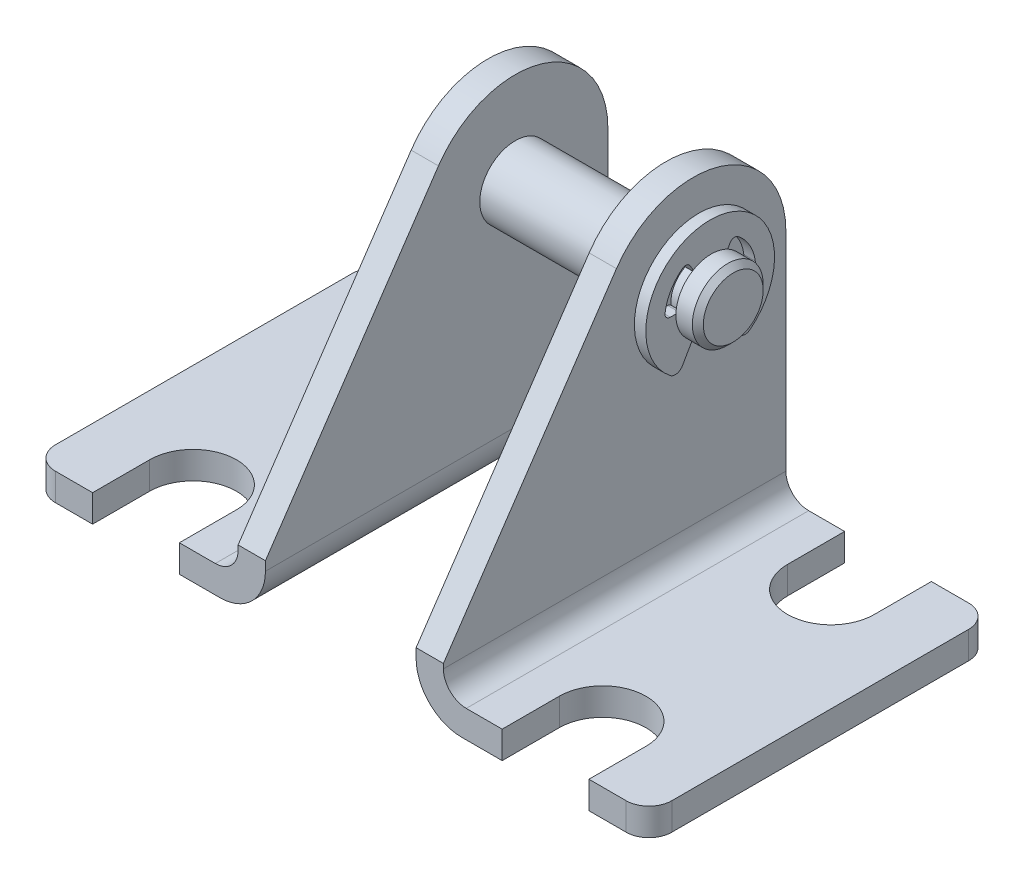
SolidWorks part; units mm, degrees
ref_plane "Front Plane" through (0, 0, 0) normal (0, 0, 1) x (1, 0, 0)
ref_plane "Top Plane" through (0, 0, 0) normal (0, 1, 0) x (1, 0, 0)
ref_plane "Right Plane" through (0, 0, 0) normal (1, 0, 0) x (0, 0, -1)
sketch "Sketch1" plane through (0, 0, 0) normal (0, 1, 0) x (1, 0, 0)
  line L0 (-17.145, 0) -> (17.145, 0) construction
  line L1 (-17.145, 5.1562) -> (-13.8049, 5.1562)
  line L2 (-17.145, 5.1562) -> (-17.145, -13.8938)
  line L3 (-17.145, -13.8938) -> (-13.8049, -13.8938)
  line L4 (17.145, 5.1562) -> (17.145, -13.8938)
  line L5 (-4.191, 5.1562) -> (-4.191, -13.8938)
  line L6 (4.191, 5.1562) -> (4.191, -13.8938)
  line L7 (4.191, 5.1562) -> (8.9789, 5.1562)
  line L8 (4.191, -13.8938) -> (8.9789, -13.8938)
  line L9 (-5.7099, 5.1562) -> (-5.7099, -13.8938) construction
  line L10 (-4.191, 5.1562) -> (4.191, 5.1562) construction
  line L11 (-4.191, -13.8938) -> (4.191, -13.8938) construction
  line L12 (0, 5.1562) -> (0, 0) construction
  line L13 (-13.8049, 1.9812) -> (-13.8049, 5.1562)
  line L14 (-8.9789, 1.9812) -> (-8.9789, 5.1562)
  line L15 (8.9789, 1.9812) -> (8.9789, 5.1562)
  line L16 (13.8049, 1.9812) -> (13.8049, 5.1562)
  line L17 (13.8049, -10.7188) -> (13.8049, -13.8938)
  line L18 (8.9789, -10.7188) -> (8.9789, -13.8938)
  line L19 (-8.9789, -10.7188) -> (-8.9789, -13.8938)
  line L20 (-13.8049, -10.7188) -> (-13.8049, -13.8938)
  line L21 (-8.9789, -13.8938) -> (-4.191, -13.8938)
  line L22 (13.8049, -13.8938) -> (17.145, -13.8938)
  line L23 (13.8049, 5.1562) -> (17.145, 5.1562)
  line L24 (-8.9789, 5.1562) -> (-4.191, 5.1562)
  line L25 (5.7099, 5.1562) -> (5.7099, -13.8938) construction
  arc A0 (-13.8049, 1.9812) -> (-8.9789, 1.9812) centre (-11.3919, 1.9812) ccw
  arc A1 (-8.9789, -10.7188) -> (-13.8049, -10.7188) centre (-11.3919, -10.7188) ccw
  arc A2 (13.8049, -10.7188) -> (8.9789, -10.7188) centre (11.3919, -10.7188) ccw
  arc A3 (8.9789, 1.9812) -> (13.8049, 1.9812) centre (11.3919, 1.9812) ccw
  dimension "D1" = 22.7838
  dimension "A" = 5.1562
  dimension "C" = 8.382
  dimension "D" = 1.5189
  dimension "K" = 34.29
  dimension "J" = 19.05
  dimension "I" = 3.175
  dimension "H" = 12.7
  dimension "G" = 4.826
sketch "Sketch2" plane through (0, 0, 0) normal (1, 0, 0) x (0, 0, -1)
  line L0 (-13.8938, 0) -> (5.1562, 0)
  line L1 (0, 14.3637) -> (0, 0) construction
  line L2 (-13.8938, 0) -> (-13.8938, 3.048)
  line L3 (-13.8938, 3.048) -> (-4.2689, 17.2556)
  line L4 (5.1562, 14.3637) -> (5.1562, 0)
  arc A0 (-4.2689, 17.2556) -> (5.1562, 14.3637) centre (0, 14.3637) cw
  circle A1 centre (0, 14.3637) radius 1.9698
  dimension "Pin Dia" = 3.9395
  dimension "D1" = 3.048
  dimension "E" = 19.5199
  dimension "F" = 14.3637
sketch "Sketch3" plane through (0, 0, 0) normal (0, 1, 0) x (1, 0, 0)
  line L12 (8.9789, -13.8938) -> (8.9789, -10.7188)
  line L13 (13.8049, -10.7188) -> (13.8049, -13.8938)
  line L14 (13.8049, -13.8938) -> (17.145, -13.8938)
  line L15 (17.145, -13.8938) -> (17.145, 5.1562)
  line L16 (17.145, 5.1562) -> (13.8049, 5.1562)
  line L17 (13.8049, 5.1562) -> (13.8049, 1.9812)
  line L18 (8.9789, 1.9812) -> (8.9789, 5.1562)
  line L19 (8.9789, 5.1562) -> (4.191, 5.1562)
  line L20 (4.191, 5.1562) -> (4.191, -13.8938)
  line L21 (4.191, -13.8938) -> (8.9789, -13.8938)
  line L22 (8.9789, -13.8938) -> (8.9789, -10.7188)
  line L23 (13.8049, -10.7188) -> (13.8049, -13.8938)
  line L24 (13.8049, -13.8938) -> (17.145, -13.8938)
  line L25 (17.145, -13.8938) -> (17.145, 5.1562)
  line L26 (17.145, 5.1562) -> (13.8049, 5.1562)
  line L27 (13.8049, 5.1562) -> (13.8049, 1.9812)
  line L28 (8.9789, 1.9812) -> (8.9789, 5.1562)
  line L29 (8.9789, 5.1562) -> (4.191, 5.1562)
  line L30 (4.191, 5.1562) -> (4.191, -13.8938)
  line L31 (4.191, -13.8938) -> (8.9789, -13.8938)
  line L32 (-17.145, -13.8938) -> (-13.8049, -13.8938)
  line L33 (-17.145, 5.1562) -> (-17.145, -13.8938)
  line L34 (-13.8049, 5.1562) -> (-17.145, 5.1562)
  line L35 (-13.8049, 1.9812) -> (-13.8049, 5.1562)
  line L36 (-8.9789, 5.1562) -> (-8.9789, 1.9812)
  line L37 (-4.191, 5.1562) -> (-8.9789, 5.1562)
  line L38 (-4.191, -13.8938) -> (-4.191, 5.1562)
  line L39 (-8.9789, -13.8938) -> (-4.191, -13.8938)
  line L40 (-8.9789, -10.7188) -> (-8.9789, -13.8938)
  line L41 (-13.8049, -13.8938) -> (-13.8049, -10.7188)
  line L42 (-17.145, -13.8938) -> (-13.8049, -13.8938)
  line L43 (-17.145, 5.1562) -> (-17.145, -13.8938)
  line L44 (-13.8049, 5.1562) -> (-17.145, 5.1562)
  line L45 (-13.8049, 1.9812) -> (-13.8049, 5.1562)
  line L46 (-8.9789, 5.1562) -> (-8.9789, 1.9812)
  line L47 (-4.191, 5.1562) -> (-8.9789, 5.1562)
  line L48 (-4.191, -13.8938) -> (-4.191, 5.1562)
  line L49 (-8.9789, -13.8938) -> (-4.191, -13.8938)
  line L50 (-8.9789, -10.7188) -> (-8.9789, -13.8938)
  line L51 (-13.8049, -13.8938) -> (-13.8049, -10.7188)
  arc A2 (13.8049, -10.7188) -> (8.9789, -10.7188) centre (11.3919, -10.7188) ccw
  arc A3 (8.9789, 1.9812) -> (13.8049, 1.9812) centre (11.3919, 1.9812) ccw
  arc A4 (13.8049, -10.7188) -> (8.9789, -10.7188) centre (11.3919, -10.7188) ccw
  arc A5 (8.9789, 1.9812) -> (13.8049, 1.9812) centre (11.3919, 1.9812) ccw
  arc A6 (-13.8049, 1.9812) -> (-8.9789, 1.9812) centre (-11.3919, 1.9812) ccw
  arc A7 (-8.9789, -10.7188) -> (-13.8049, -10.7188) centre (-11.3919, -10.7188) ccw
  arc A8 (-13.8049, 1.9812) -> (-8.9789, 1.9812) centre (-11.3919, 1.9812) ccw
  arc A9 (-8.9789, -10.7188) -> (-13.8049, -10.7188) centre (-11.3919, -10.7188) ccw
  dimension "D1" = 0
  dimension "D2" = 0
extrude "Boss-Extrude1" add sketch "Sketch3" along normal blind 1.5189
sketch "Sketch4" plane through (-4.191, 0, 0) normal (1, 0, 0) x (0, 0, -1)
  line L6 (-13.8938, 0) -> (5.1562, 0)
  line L7 (5.1562, 0) -> (5.1562, 14.3637)
  line L8 (-4.2689, 17.2556) -> (-13.8938, 3.048)
  line L12 (-13.8938, 3.048) -> (-13.8938, 0)
  line L13 (-13.8938, 0) -> (5.1562, 0)
  line L14 (5.1562, 0) -> (5.1562, 14.3637)
  line L15 (-4.2689, 17.2556) -> (-13.8938, 3.048)
  line L16 (-13.8938, 3.048) -> (-13.8938, 0)
  circle A1 centre (0, 14.3637) radius 1.9698
  circle A3 centre (0, 14.3637) radius 1.9698
  arc A5 (5.1562, 14.3637) -> (-4.2689, 17.2556) centre (0, 14.3637) ccw
  arc A6 (5.1562, 14.3637) -> (-4.2689, 17.2556) centre (0, 14.3637) ccw
  dimension "D1" = 0
  dimension "D2" = 0
extrude "Boss-Extrude2" add sketch "Sketch4" against normal up to vertex (1.5189 mm away) up to point (-5.7099, 0, -5.1562)
sketch "Sketch5" plane through (4.191, 0, 0) normal (-1, 0, 0) x (0, 0, 1)
  line L4 (-5.1562, 0) -> (13.8938, 0)
  line L5 (-5.1562, 14.3637) -> (-5.1562, 0)
  line L6 (13.8938, 3.048) -> (4.2689, 17.2556)
  line L7 (13.8938, 0) -> (13.8938, 3.048)
  line L8 (-5.1562, 0) -> (13.8938, 0)
  line L9 (-5.1562, 14.3637) -> (-5.1562, 0)
  line L10 (13.8938, 3.048) -> (4.2689, 17.2556)
  line L11 (13.8938, 0) -> (13.8938, 3.048)
  circle A1 centre (0, 14.3637) radius 1.9698
  circle A2 centre (0, 14.3637) radius 1.9698
  arc A3 (4.2689, 17.2556) -> (-5.1562, 14.3637) centre (0, 14.3637) ccw
  arc A4 (4.2689, 17.2556) -> (-5.1562, 14.3637) centre (0, 14.3637) ccw
  dimension "D1" = 0
  dimension "D2" = 0
extrude "Boss-Extrude3" add sketch "Sketch5" against normal up to vertex (1.5189 mm away) up to point (5.7099, 0, -5.1562)
fillet "Fillet1" radius 1.27 3 edges at (-5.7099, 1.5189, 4.3688) (-17.145, 0.7595, -5.1562) (-17.145, 0.7595, 13.8938)
fillet "Fillet2" radius 2.54 1 edges at (-4.191, 0, 4.3688)
fillet "Fillet3" radius 1.27 3 edges at (5.7099, 1.5189, 4.3688) (17.145, 0.7595, -5.1562) (17.145, 0.7595, 13.8938)
fillet "Fillet4" radius 2.54 1 edges at (4.191, 0, 4.3688)
sketch "Sketch6" plane through (0, 0, 0) normal (0, 0, 1) x (1, 0, 0)
  line L0 (0, 14.3637) -> (0, 16.3335) construction
  line L1 (-7.6327, 16.3335) -> (-6.7183, 16.3335)
  line L2 (-7.9375, 16.0287) -> (-7.9375, 14.3637)
  line L3 (-7.9375, 14.3637) -> (7.9375, 14.3637)
  line L4 (7.9375, 16.0287) -> (7.9375, 14.3637)
  line L8 (-7.9375, 16.0287) -> (-7.6327, 16.3335)
  line L9 (-6.7183, 16.3335) -> (-6.7183, 15.8496)
  line L10 (-6.7183, 15.8496) -> (-5.9563, 15.8496)
  line L11 (-5.9563, 15.8496) -> (-5.9563, 16.3335)
  line L12 (5.9563, 16.3335) -> (5.9563, 15.8496)
  line L13 (5.9563, 15.8496) -> (6.7183, 15.8496)
  line L14 (6.7183, 15.8496) -> (6.7183, 16.3335)
  line L15 (7.6327, 16.3335) -> (7.9375, 16.0287)
  line L16 (-5.9563, 16.3335) -> (5.9563, 16.3335)
  line L17 (6.7183, 16.3335) -> (7.6327, 16.3335)
  line L18 (-7.9375, 16.0287) -> (-7.9375, 16.3335) construction
  line L19 (-7.9375, 16.3335) -> (-7.6327, 16.3335) construction
  line L20 (-6.7183, 16.3335) -> (-5.9563, 16.3335) construction
  line L21 (5.9563, 16.3335) -> (6.7183, 16.3335) construction
  line L22 (7.6327, 16.3335) -> (7.9375, 16.3335) construction
  line L23 (7.9375, 16.3335) -> (7.9375, 16.0287) construction
  line L24 (-7.9375, 14.3637) -> (7.9375, 14.3637) construction
  line L25 (-6.3373, 15.8496) -> (-6.3373, 14.3637) construction
  point P22 (-6.3373, 14.3637)
  dimension "Gap OD" = 2.9718
  dimension "Gap" = 0.762
  dimension "Chamfer" = 0.3048
  dimension "Pin Lg." = 15.875
  dimension "Center Lg." = 11.9126
revolve "Revolve1" add sketch "Sketch6" angle 360 about L24
ref_plane "Plane1" through (-6.3373, 0, 0) normal (1, 0, 0) x (0, 0, -1)
sketch "Sketch7" plane through (-6.3373, 0, 0) normal (1, 0, 0) x (0, 0, -1)
  line L0 (0, 14.3637) -> (0, 15.8496) construction
  line L1 (0, 14.3637) -> (0.8637, 15.8597) construction
  line L2 (0.8637, 15.8597) -> (1.1076, 16.2821)
  line L3 (0, 14.3637) -> (1.7274, 14.3637) construction
  line L4 (1.7274, 14.3637) -> (2.2152, 14.3637)
  line L5 (0, 14.3637) -> (0.7429, 13.0769) construction
  line L6 (0.8637, 12.8677) -> (1.5508, 11.6776)
  line L7 (-0.8637, 12.8677) -> (-1.5508, 11.6776)
  line L8 (0, 14.3637) -> (-0.7429, 13.0769) construction
  line L9 (0, 15.8496) -> (0, 16.8974) construction
  line L10 (0, 16.8974) -> (0, 17.9451) construction
  line L11 (-1.7274, 14.3637) -> (-2.2152, 14.3637)
  line L12 (-0.8637, 15.8597) -> (-1.1076, 16.2821)
  circle A0 centre (0, 14.3637) radius 1.4859 construction
  circle A1 centre (0, 14.3637) radius 3.5814 construction
  arc A2 (2.511, 14.702) -> (1.5485, 16.3691) centre (0, 14.3637) ccw
  arc A3 (0.5423, 15.7471) -> (-0.5423, 15.7471) centre (0, 14.3637) ccw
  arc A4 (2.2154, 11.5497) -> (-2.2154, 11.5497) centre (0, 14.3637) ccw
  arc A5 (0.927, 13.2024) -> (1.4692, 14.1416) centre (0, 14.3637) ccw
  circle A6 centre (0, 14.3637) radius 2.5336 construction
  arc A7 (1.5508, 11.6776) -> (2.2154, 11.5497) centre (1.9385, 11.9015) ccw
  arc A8 (-1.5508, 11.6776) -> (-2.2154, 11.5497) centre (-1.9385, 11.9015) cw
  arc A9 (1.5485, 16.3691) -> (1.1076, 16.2821) centre (1.3661, 16.1329) ccw
  arc A10 (2.511, 14.702) -> (2.2152, 14.3637) centre (2.2152, 14.6622) cw
  arc A11 (0.8637, 12.8677) -> (0.927, 13.2024) centre (1.0899, 12.9983) cw
  arc A12 (0.5423, 15.7471) -> (0.8637, 15.8597) centre (0.6376, 15.9903) ccw
  arc A13 (1.7274, 14.3637) -> (1.4692, 14.1416) centre (1.7274, 14.1026) ccw
  arc A14 (-0.8637, 12.8677) -> (-0.927, 13.2024) centre (-1.0899, 12.9983) ccw
  arc A15 (-0.927, 13.2024) -> (-1.4692, 14.1416) centre (0, 14.3637) cw
  arc A16 (-1.7274, 14.3637) -> (-1.4692, 14.1416) centre (-1.7274, 14.1026) cw
  arc A17 (-2.511, 14.702) -> (-2.2152, 14.3637) centre (-2.2152, 14.6622) ccw
  arc A18 (-2.511, 14.702) -> (-1.5485, 16.3691) centre (0, 14.3637) cw
  arc A19 (-1.5485, 16.3691) -> (-1.1076, 16.2821) centre (-1.3661, 16.1329) cw
  arc A20 (-0.5423, 15.7471) -> (-0.8637, 15.8597) centre (-0.6376, 15.9903) cw
  point P18 (1.7907, 11.2621)
  point P21 (-1.7907, 11.2621)
  point P26 (2.5336, 14.3637)
  dimension "D1" = 30
  dimension "OD" = 7.1628
  dimension "ID" = 2.9718
  dimension "D2" = 0.4477
  dimension "D4" = 0.2984
  dimension "D5" = 0.2611
  dimension "D3" = 30
extrude "Boss-Extrude5" add sketch "Sketch7" along normal mid plane 0.635 separate body
mirror "Mirror1" about plane through (0, 0, 0) normal (1, 0, 0) of bodies 112
equation "\"D1@Boss-Extrude1\" = \"D@Sketch1\""
equation "\"D1@Fillet2\" = \"D1@Fillet1\" * 2"
equation "\"D1@Fillet3\" = \"D1@Fillet1\""
equation "\"D1@Fillet4\" = \"D1@Fillet2\""
equation "\"D2@Sketch7\" = \"OD@Sketch7\" * 1 / 16"
equation "\"D4@Sketch7\" = \"D2@Sketch7\" * 2 / 3"
equation "\"D5@Sketch7\" = \"D4@Sketch7\" * 7 / 8"
